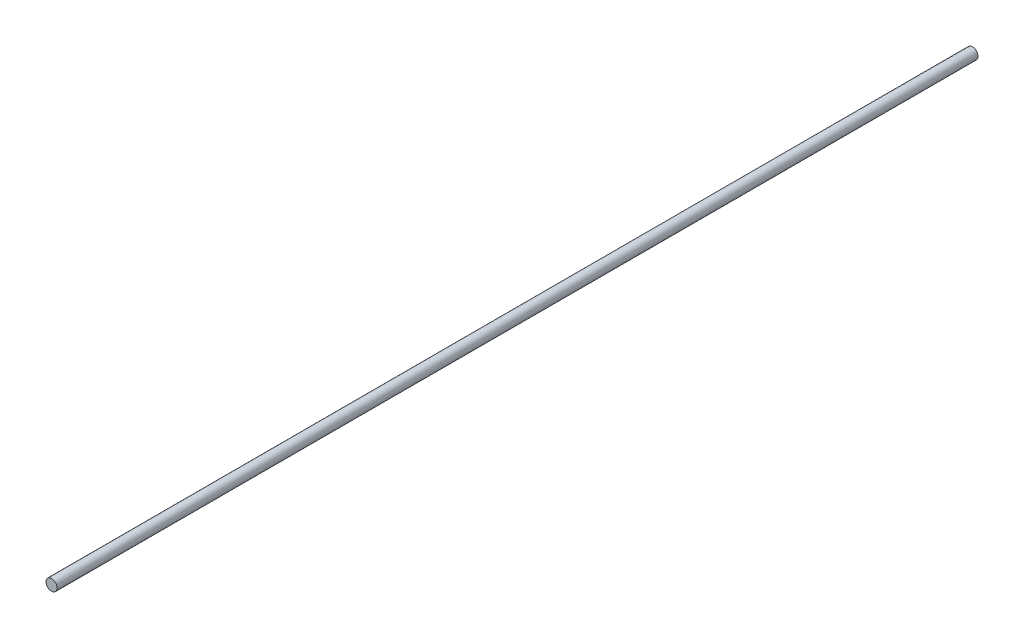
SolidWorks part; units mm, degrees
material "Chrome Stainless Steel"
ref_plane "Front Plane" through (0, 0, 0) normal (0, 0, 1) x (1, 0, 0)
ref_plane "Top Plane" through (0, 0, 0) normal (0, 1, 0) x (1, 0, 0)
ref_plane "Right Plane" through (0, 0, 0) normal (1, 0, 0) x (0, 0, -1)
sketch "Sketch1" plane through (0, 0, 0) normal (0, 0, 1) x (1, 0, 0)
  circle A0 centre (0, 0) radius 9.779
extrude "Boss-Extrude1" add sketch "Sketch1" along normal blind 1625
